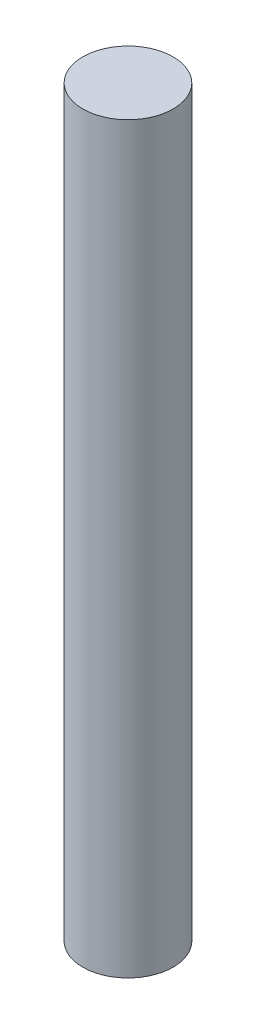
SolidWorks part; units mm, degrees
ref_plane "Front Plane" through (0, 0, 0) normal (0, 0, 1) x (1, 0, 0)
ref_plane "Top Plane" through (0, 0, 0) normal (0, 1, 0) x (1, 0, 0)
ref_plane "Right Plane" through (0, 0, 0) normal (1, 0, 0) x (0, 0, -1)
sketch "Sketch1" plane through (0, 0, 0) normal (0, 1, 0) x (1, 0, 0)
  circle A0 centre (0, 0) radius 1.75
  dimension "D1" = 3.5
extrude "Boss-Extrude1" add sketch "Sketch1" along normal blind 28.8
